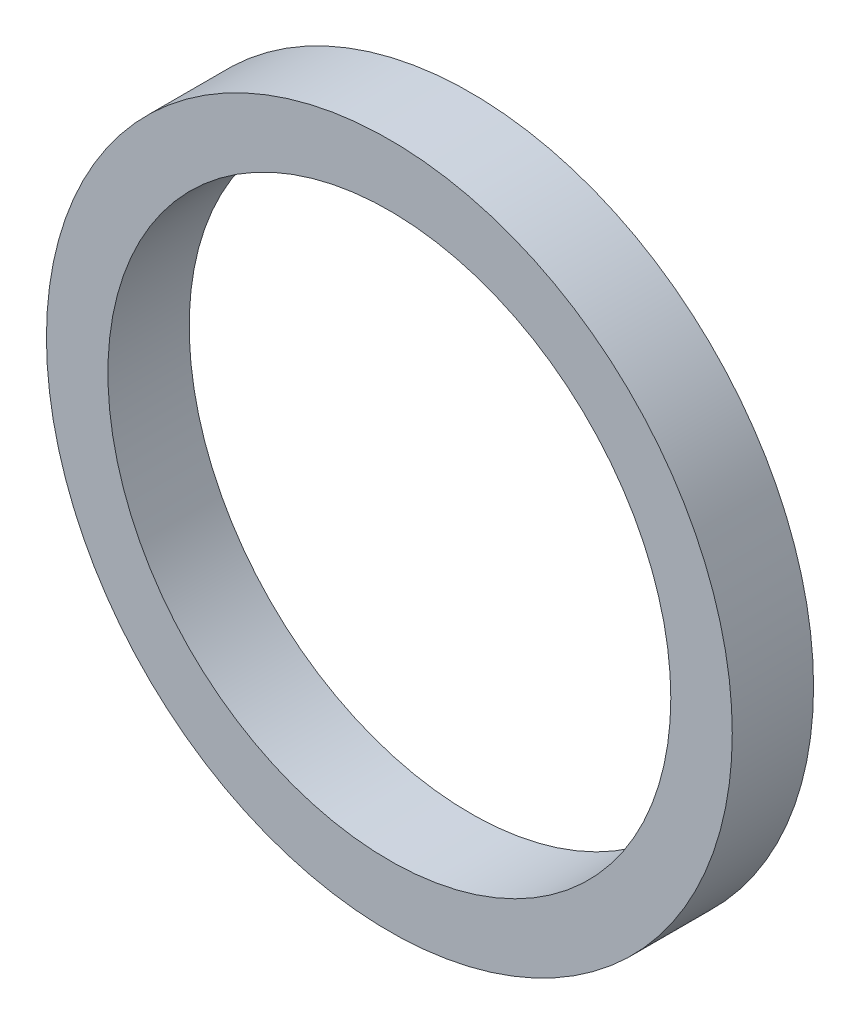
SolidWorks part; units mm, degrees
ref_plane "Front Plane" through (0, 0, 0) normal (0, 0, 1) x (1, 0, 0)
ref_plane "Top Plane" through (0, 0, 0) normal (0, 1, 0) x (1, 0, 0)
ref_plane "Right Plane" through (0, 0, 0) normal (1, 0, 0) x (0, 0, -1)
sketch "Sketch1" plane through (0, 0, 0) normal (0, 0, 1) x (1, 0, 0)
  circle A0 centre (0, 0) radius 5.54
  circle A1 centre (0, 0) radius 6.75
extrude "Boss-Extrude1" add sketch "Sketch1" along normal blind 1.6
